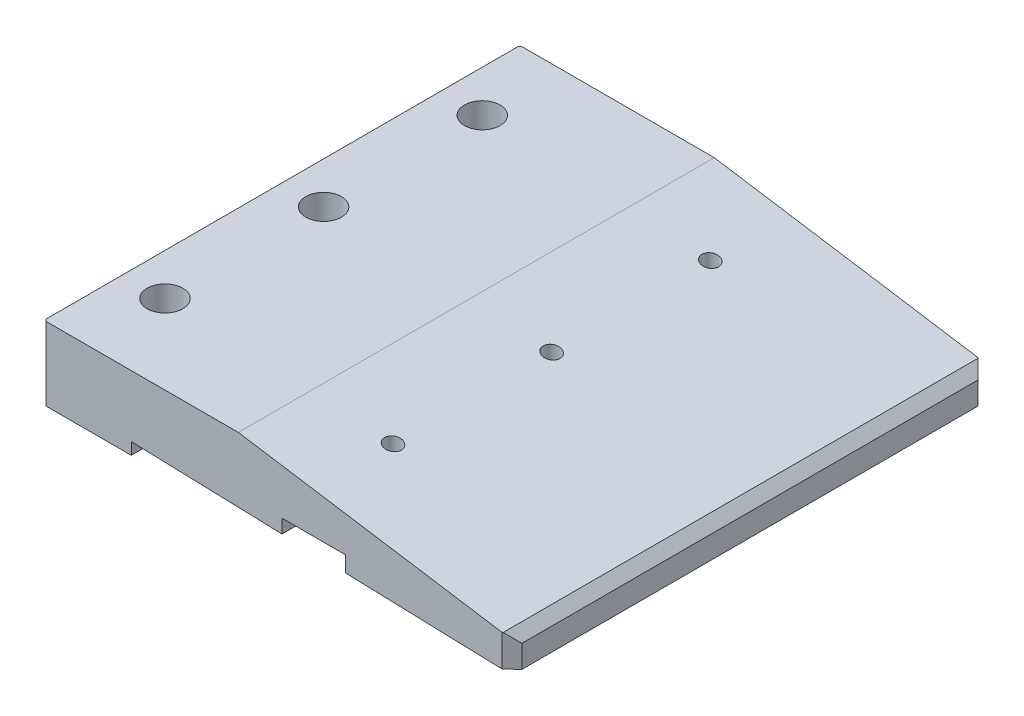
SolidWorks part; units mm, degrees
ref_plane "前视基准面" through (0, 0, 0) normal (0, 0, 1) x (1, 0, 0)
ref_plane "上视基准面" through (0, 0, 0) normal (0, 1, 0) x (1, 0, 0)
ref_plane "右视基准面" through (0, 0, 0) normal (1, 0, 0) x (0, 0, -1)
sketch "草图1" plane through (0, 0, 0) normal (0, 0, 1) x (1, 0, 0)
  line L0 (0, 0) -> (51, 0)
  line L2 (120, -10.8) -> (120, -18.5)
  line L3 (120, -18.5) -> (78, -17.1875)
  line L4 (78, -17.1875) -> (78, -13.2175)
  line L5 (78, -13.2175) -> (62, -13.2175)
  line L6 (62, -13.2175) -> (62, -16.6875)
  line L7 (62, -16.6875) -> (24, -15.5)
  line L8 (24, -15.5) -> (24, -18.5)
  line L9 (24, -18.5) -> (0, -18.5)
  line L10 (0, -18.5) -> (0, 0)
  line L13 (51, 0) -> (120, -10.8)
  point P9 (120, -18.5)
  point P13 (62, -16.8815)
  point P14 (0, 0)
  point P15 (62, -17.2124)
  point P16 (78, -12.0036)
  point P17 (78, -17.439)
  dimension "D1" = 51
  dimension "D2" = 24
  dimension "D3" = 18.5
  dimension "D4" = 3
  dimension "D5" = 38
  dimension "D6" = 16
  dimension "D7" = 120
  dimension "D8" = 7.7
  dimension "D9" = 3.97
extrude "凸台-拉伸1" add sketch "草图1" along normal blind 120
hole_wizard "孔1" positions "草图3" profile "草图4" legacy end condition through all
sketch "草图3" plane through (0, -18.5, 0) normal (0, -1, 0) x (-1, 0, 0)
  line L0 (0, -120) -> (0, 0) construction
  point P0 (-12.5, -20)
  point P2 (-12.5, -60)
  point P4 (-12.5, -100)
  point P9 (0, 0)
  point P10 (0, -60)
  dimension "D1" = 12.5
  dimension "D2" = 40
  dimension "D3" = 40
sketch "草图4" plane through (12.5, -18.5, 20) normal (1, 0, 0) x (0, 0, -1)
  line L0 (0, 0) -> (0, 18.5)
  line L1 (0, 18.5) -> (4.5, 18.5)
  line L2 (4.5, 18.5) -> (4.5, 9)
  line L3 (4.5, 9) -> (7.5, 9)
  line L4 (7.5, 9) -> (7.5, 0)
  line L5 (7.5, 0) -> (0, 0)
  line L6 (0, 110) -> (0, -10) construction
  dimension "直径" = 9
  dimension "深度" = 18.5
  dimension "柱坑直径" = 15
  dimension "柱坑深度" = 9
sketch "草图6" plane through (0, -13.2175, 0) normal (0, -1, 0) x (1, 0, 0)
  line L0 (0, 120) -> (0, 0) construction
  circle A0 centre (70, 100) radius 2.1
  circle A1 centre (70, 60) radius 2.1
  circle A2 centre (70, 20) radius 2.1
  circle A4 centre (12.5, 100) radius 4.5 construction
  point P8 (0, 0)
  point P9 (69.0878, 60)
  point P10 (0, 0)
  point P13 (0, 60)
  dimension "D1" = 57.5
  dimension "D4" = 4.2
  dimension "D2" = 40
  dimension "D3" = 40
extrude "切除-拉伸1" cut sketch "草图6" against normal up to next
chamfer "倒角2" distance 2.5 4 edges at (0, -9.25, 0) (120, -14.65, 0) (120, -14.65, 120) (0, -9.25, 120)
chamfer "倒角3" distance 2 angle 45 1 edges at (120, -10.8, 60)
chamfer "倒角4" distance 2 1 edges at (0, 0, 60)
